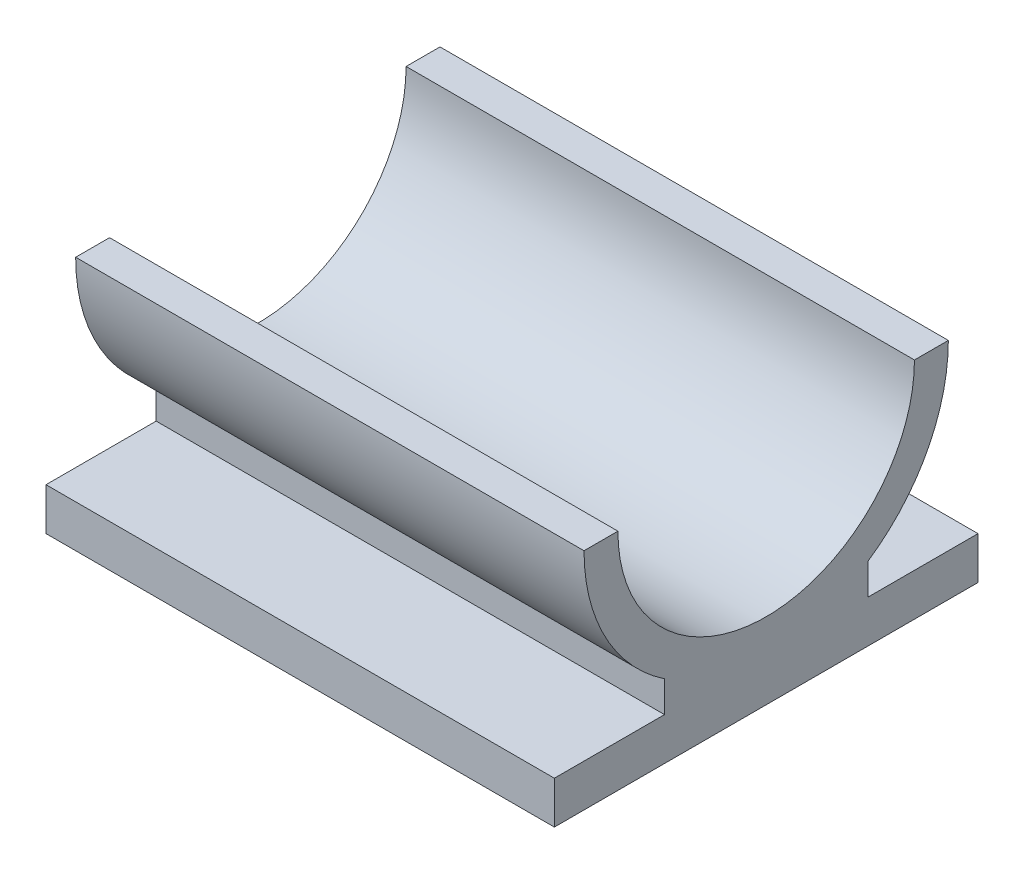
SolidWorks part; units mm, degrees
ref_plane "Front Plane" through (0, 0, 0) normal (0, 0, 1) x (1, 0, 0)
ref_plane "Top Plane" through (0, 0, 0) normal (0, 1, 0) x (1, 0, 0)
ref_plane "Right Plane" through (0, 0, 0) normal (1, 0, 0) x (0, 0, -1)
sketch "Sketch1" plane through (0, 0, 0) normal (0, 1, 0) x (1, 0, 0)
  line L1 (-38.1, -31.75) -> (38.1, -31.75)
  line L2 (-38.1, -31.75) -> (-38.1, 31.75)
  line L3 (-38.1, 31.75) -> (38.1, 31.75)
  line L4 (38.1, -31.75) -> (38.1, 31.75)
  line L5 (-38.1, -31.75) -> (38.1, 31.75) construction
  line L6 (-38.1, 31.75) -> (38.1, -31.75) construction
  point P0 (0, 0)
  dimension "D1" = 76.2
  dimension "D2" = 63.5
extrude "Boss-Extrude1" add sketch "Sketch1" along normal blind 6.35
sketch "Sketch2" plane through (38.1, 0, 0) normal (1, 0, 0) x (0, 0, -1)
  line L0 (-31.75, 6.35) -> (31.75, 6.35) construction
  line L1 (-27.305, 33.655) -> (-22.225, 33.655)
  line L2 (22.225, 33.655) -> (27.305, 33.655)
  arc A0 (-22.225, 33.655) -> (22.225, 33.655) centre (0, 33.655) ccw
  arc A1 (-27.305, 33.655) -> (27.305, 33.655) centre (0, 33.655) ccw
  point P9 (0, 33.655)
  dimension "D1" = 44.45
  dimension "D2" = 5.08
extrude "Boss-Extrude2" add sketch "Sketch2" against normal blind 76.2 separate body
sketch "Sketch3" plane through (38.1, 0, 0) normal (1, 0, 0) x (0, 0, -1)
  line L0 (-31.75, 6.35) -> (31.75, 6.35) construction
  line L1 (-15.24, 11.176) -> (15.24, 11.176)
  line L2 (-15.24, 11.176) -> (-15.24, 6.35)
  line L3 (-15.24, 6.35) -> (15.24, 6.35)
  line L4 (15.24, 11.176) -> (15.24, 6.35)
  line L5 (-15.24, 11.176) -> (15.24, 6.35) construction
  line L6 (-15.24, 6.35) -> (15.24, 11.176) construction
  point P0 (0, 8.763)
  point P7 (0, 0)
  dimension "D1" = 30.48
  dimension "D2" = 4.826
extrude "Boss-Extrude3" add sketch "Sketch3" against normal blind 76.2
